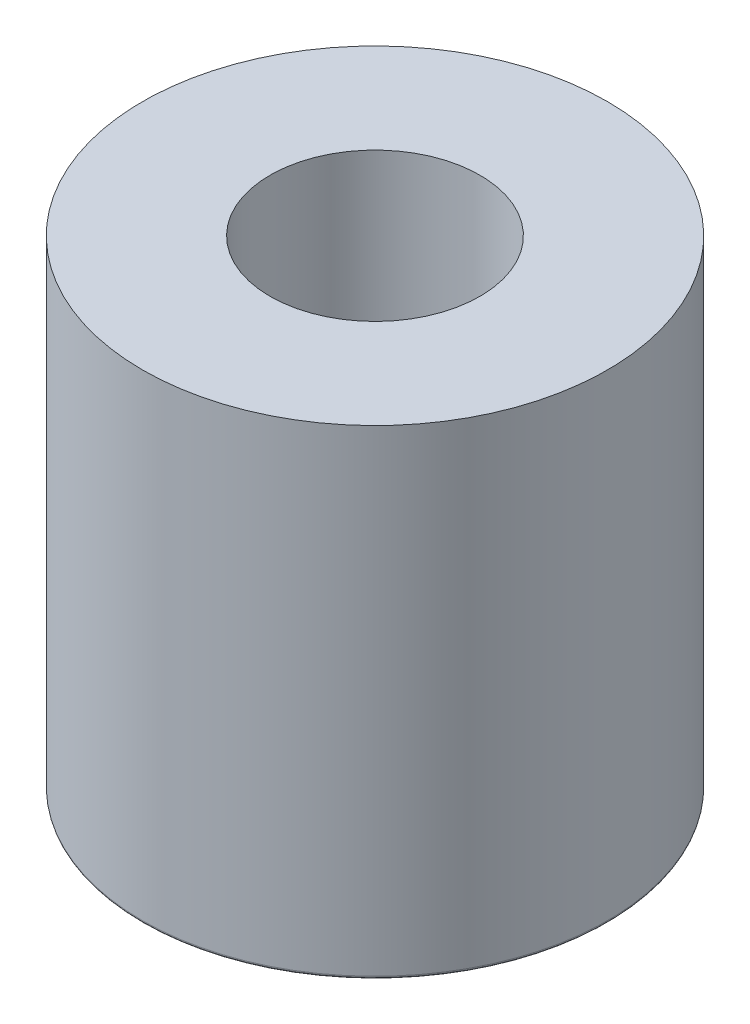
SolidWorks part; units mm, degrees
ref_plane "Front Plane" through (0, 0, 0) normal (0, 0, 1) x (1, 0, 0)
ref_plane "Top Plane" through (0, 0, 0) normal (0, 1, 0) x (1, 0, 0)
ref_plane "Right Plane" through (0, 0, 0) normal (1, 0, 0) x (0, 0, -1)
sketch "Sketch1" plane through (0, 0, 0) normal (0, 1, 0) x (1, 0, 0)
  circle A0 centre (0, 0) radius 3
extrude "Boss-Extrude1" add sketch "Sketch1" along normal blind 4.5
sketch "Sketch2" plane through (0, 0, 0) normal (0, -1, 0) x (1, 0, 0)
  circle A0 centre (0, 0) radius 4
extrude "Boss-Extrude3" add sketch "Sketch2" along normal blind 5.7
sketch "Sketch3" plane through (0, -5.7, 0) normal (0, -1, 0) x (1, 0, 0)
  circle A0 centre (0, 0) radius 3.875
extrude "Boss-Extrude4" add sketch "Sketch3" along normal blind 6
sketch "Sketch4" plane through (0, 4.5, 0) normal (0, 1, 0) x (1, 0, 0)
  circle A0 centre (0, 0) radius 1.75
extrude "Cut-Extrude1" cut sketch "Sketch4" against normal blind 15
sketch "Sketch27" plane through (0, -11.7, 0) normal (0, -1, 0) x (1, 0, 0)
  line L0 (0, 0) -> (0, -3.1135) construction
  line L3 (2.7, 1) -> (2.9, 1)
  line L4 (2.7, 1) -> (2.7, -1)
  line L5 (2.7, -1) -> (2.9, -1)
  line L6 (2.9, 1) -> (2.9, -1)
  line L7 (2.4396, 1) -> (2.2396, 1)
  line L8 (2.4396, 1) -> (2.4396, -1)
  line L9 (2.4396, -1) -> (2.2396, -1)
  line L10 (2.2396, 1) -> (2.2396, -1)
  line L11 (-2.2396, 1) -> (-2.2396, -1)
  line L12 (-2.4396, -1) -> (-2.2396, -1)
  line L13 (-2.4396, 1) -> (-2.4396, -1)
  line L14 (-2.4396, 1) -> (-2.2396, 1)
  line L15 (-2.9, 1) -> (-2.9, -1)
  line L16 (-2.7, -1) -> (-2.9, -1)
  line L17 (-2.7, 1) -> (-2.7, -1)
  line L18 (-2.7, 1) -> (-2.9, 1)
  text T0 "3     2" font "Lucida Bright" height in points 4
  text T1 "1" font "Lucida Bright" height in points 4
extrude "Boss-Extrude11" add sketch "Sketch27" along normal blind 0.1
sketch "Sketch28" plane through (0, -11.7, 0) normal (0, -1, 0) x (1, 0, 0)
  line L0 (0, 2.275) -> (0, 0) construction
  line L1 (1, 2.585) -> (1, 2.265)
  line L2 (-1, 2.585) -> (-1, 2.265)
  line L3 (-1, 2.265) -> (1, 2.265)
  line L4 (2.4396, 1) -> (2.4396, -1)
  line L5 (2.7, -1) -> (2.4396, -1)
  line L6 (2.7, 1) -> (2.7, -1)
  line L7 (1, 2.585) -> (-1, 2.585)
  line L8 (2.7, 1) -> (2.4396, 1)
  line L13 (-2.7, 1) -> (-2.4396, 1)
  line L14 (-2.7, 1) -> (-2.7, -1)
  line L15 (-2.7, -1) -> (-2.4396, -1)
  line L16 (-2.4396, 1) -> (-2.4396, -1)
extrude "Cut-Extrude12" cut sketch "Sketch28" against normal blind 2
sketch "Sketch29" plane through (0, 0, 0) normal (0, 0, 1) x (1, 0, 0)
  line L0 (0, 0) -> (0, -8.2342) construction
  line L1 (0, -3.7) -> (3.875, -3.7)
  line L2 (3.875, -3.7) -> (3.875, -5.7)
  line L3 (3.875, -5.7) -> (4.9494, -5.7)
  line L4 (4.9494, -5.7) -> (4.9494, 6.2895)
  line L5 (4.9494, 6.2895) -> (0, 6.2895)
  line L6 (0, -3.7) -> (0, 6.2895)
revolve "Cut-Revolve2" cut sketch "Sketch29" angle 360 about L0
sketch "Sketch30" plane through (0, -10.5, 0) normal (0, 1, 0) x (1, 0, 0)
  circle A0 centre (0, 0) radius 0.75
extrude "Boss-Extrude12" add sketch "Sketch30" along normal blind 0.25
fillet "Fillet1" radius 0.05 1 edges at (0, -11.7, -3.875)
